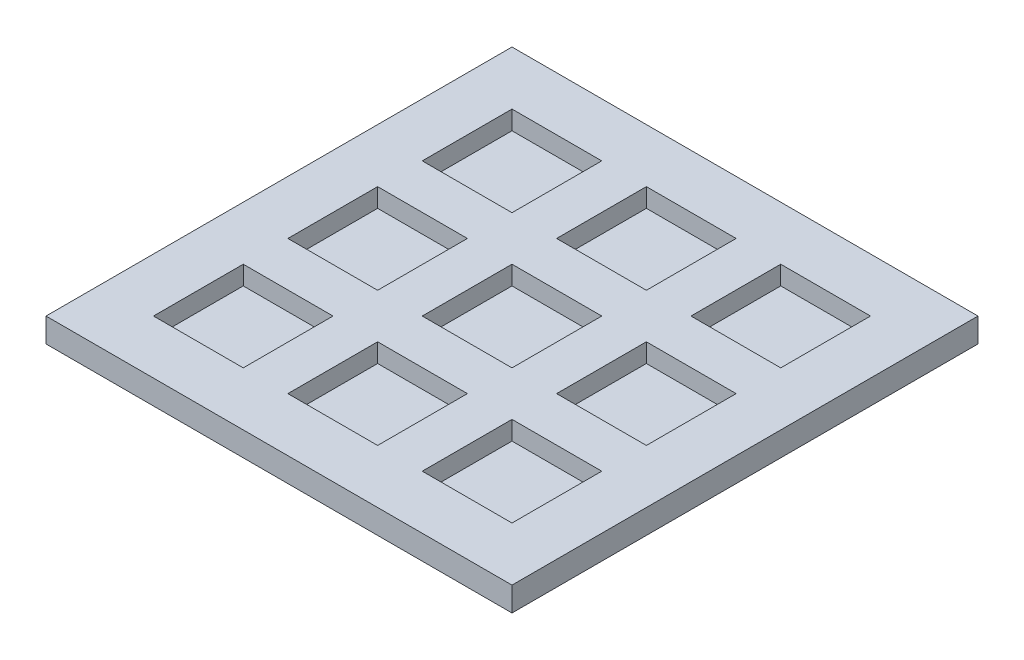
SolidWorks part; units mm, degrees
ref_plane "Plan de face" through (0, 0, 0) normal (0, 0, 1) x (1, 0, 0)
ref_plane "Plan de dessus" through (0, 0, 0) normal (0, 1, 0) x (1, 0, 0)
ref_plane "Plan de droite" through (0, 0, 0) normal (1, 0, 0) x (0, 0, -1)
sketch "Esquisse1" plane through (0, 0, 0) normal (0, 1, 0) x (1, 0, 0)
  line L0 (35, 26.7) -> (51.7, 26.7)
  line L1 (0, 0) -> (86.7, 0)
  line L2 (0, 0) -> (0, 86.7)
  line L3 (0, 86.7) -> (86.7, 86.7)
  line L4 (86.7, 0) -> (86.7, 86.7)
  line L5 (10, 10) -> (26.7, 10)
  line L6 (10, 10) -> (10, 26.7)
  line L7 (10, 26.7) -> (26.7, 26.7)
  line L8 (26.7, 10) -> (26.7, 26.7)
  line L9 (35, 10) -> (35, 26.7)
  line L10 (35, 10) -> (51.7, 10)
  line L11 (51.7, 10) -> (51.7, 26.7)
  line L12 (60, 26.7) -> (76.7, 26.7)
  line L13 (60, 10) -> (60, 26.7)
  line L14 (60, 10) -> (76.7, 10)
  line L15 (76.7, 10) -> (76.7, 26.7)
  line L16 (35, 51.7) -> (51.7, 51.7)
  line L17 (35, 35) -> (35, 51.7)
  line L18 (35, 35) -> (51.7, 35)
  line L19 (51.7, 35) -> (51.7, 51.7)
  line L20 (60, 51.7) -> (76.7, 51.7)
  line L21 (60, 35) -> (60, 51.7)
  line L22 (60, 35) -> (76.7, 35)
  line L23 (76.7, 35) -> (76.7, 51.7)
  line L24 (35, 76.7) -> (51.7, 76.7)
  line L25 (35, 60) -> (35, 76.7)
  line L26 (35, 60) -> (51.7, 60)
  line L27 (51.7, 60) -> (51.7, 76.7)
  line L28 (60, 76.7) -> (76.7, 76.7)
  line L29 (60, 60) -> (60, 76.7)
  line L30 (60, 60) -> (76.7, 60)
  line L31 (76.7, 60) -> (76.7, 76.7)
  line L32 (10, 51.7) -> (26.7, 51.7)
  line L33 (10, 35) -> (10, 51.7)
  line L34 (10, 35) -> (26.7, 35)
  line L35 (26.7, 35) -> (26.7, 51.7)
  line L36 (10, 76.7) -> (26.7, 76.7)
  line L37 (10, 60) -> (10, 76.7)
  line L38 (10, 60) -> (26.7, 60)
  line L39 (26.7, 60) -> (26.7, 76.7)
  line L40 (10, 26.7) -> (10, 51.7) construction
  point P9 (0, 0)
  point P10 (22.4678, 76.5206)
  point P11 (0, 0)
  dimension "D1" = 10
  dimension "D2" = 10
  dimension "D3" = 16.7
  dimension "D4" = 25
  dimension "D7" = 25
  dimension "D8" = 10
  dimension "D9" = 10
  dimension "D5" = 3
  dimension "D6" = 3
extrude "Boss.-Extru.1" add sketch "Esquisse1" along normal blind 3.5
sketch "Esquisse2" plane through (0, 0, 0) normal (0, -1, 0) x (1, 0, 0)
  line L1 (0, 0) -> (86.7, 0)
  line L2 (0, 0) -> (0, -86.7)
  line L3 (0, -86.7) -> (86.7, -86.7)
  line L4 (86.7, 0) -> (86.7, -86.7)
extrude "Boss.-Extru.2" add sketch "Esquisse2" along normal blind 1
